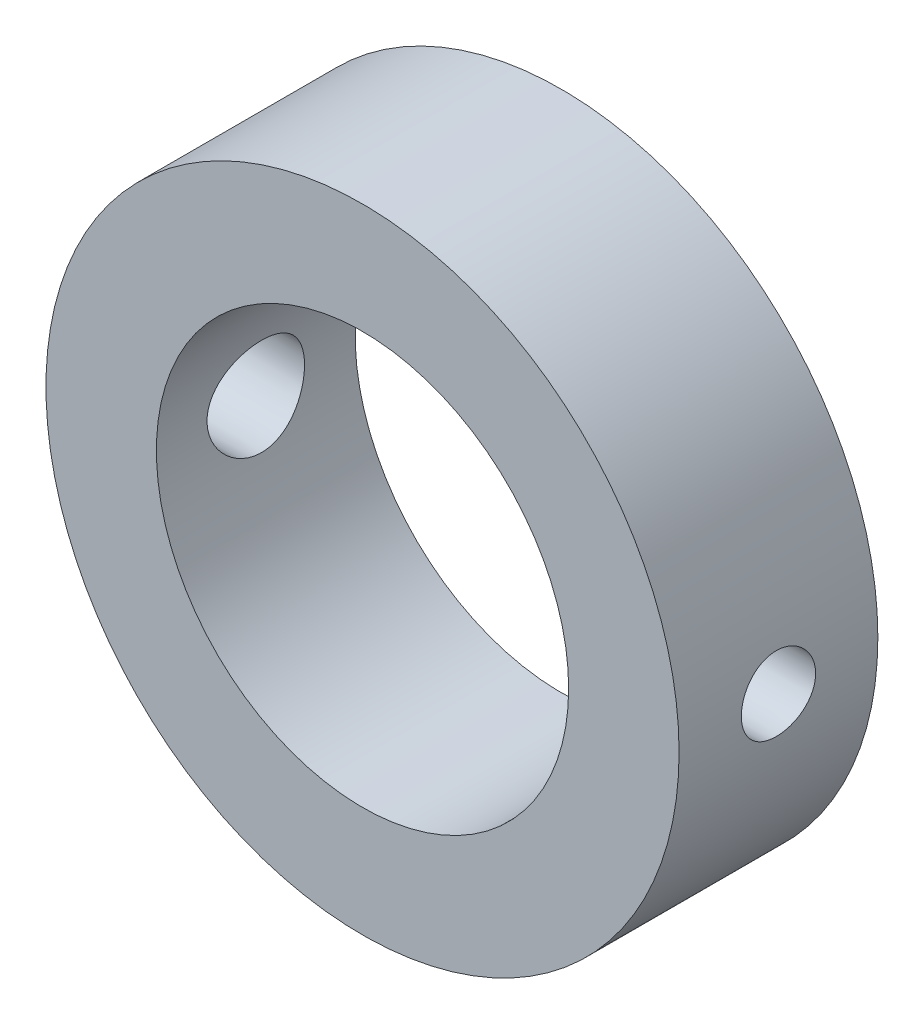
SolidWorks part; units mm, degrees
ref_plane "Front Plane" through (0, 0, 0) normal (0, 0, 1) x (1, 0, 0)
ref_plane "Top Plane" through (0, 0, 0) normal (0, 1, 0) x (1, 0, 0)
ref_plane "Right Plane" through (0, 0, 0) normal (1, 0, 0) x (0, 0, -1)
sketch "Sketch1" plane through (0, 0, 0) normal (0, 0, 1) x (1, 0, 0)
  circle A0 centre (0, 0) radius 28
  circle A1 centre (0, 0) radius 43
  dimension "D1" = 86
  dimension "D2" = 56
extrude "Boss-Extrude1" add sketch "Sketch1" along normal mid plane 27
sketch "Sketch4" plane through (0, 0, 0) normal (0, 1, 0) x (1, 0, 0)
  line L0 (0, 0) -> (-55.4463, 0) construction
  line L1 (-45, 0) -> (-45, 7)
  line L2 (-45, 7) -> (45, 5)
  line L3 (45, 5) -> (45, 0)
  line L4 (45, 0) -> (-45, 0)
  dimension "D1" = 7
  dimension "D2" = 5
  dimension "D3" = 45
  dimension "D4" = 90
revolve "Cut-Revolve1" cut sketch "Sketch4" angle 360 about L0
